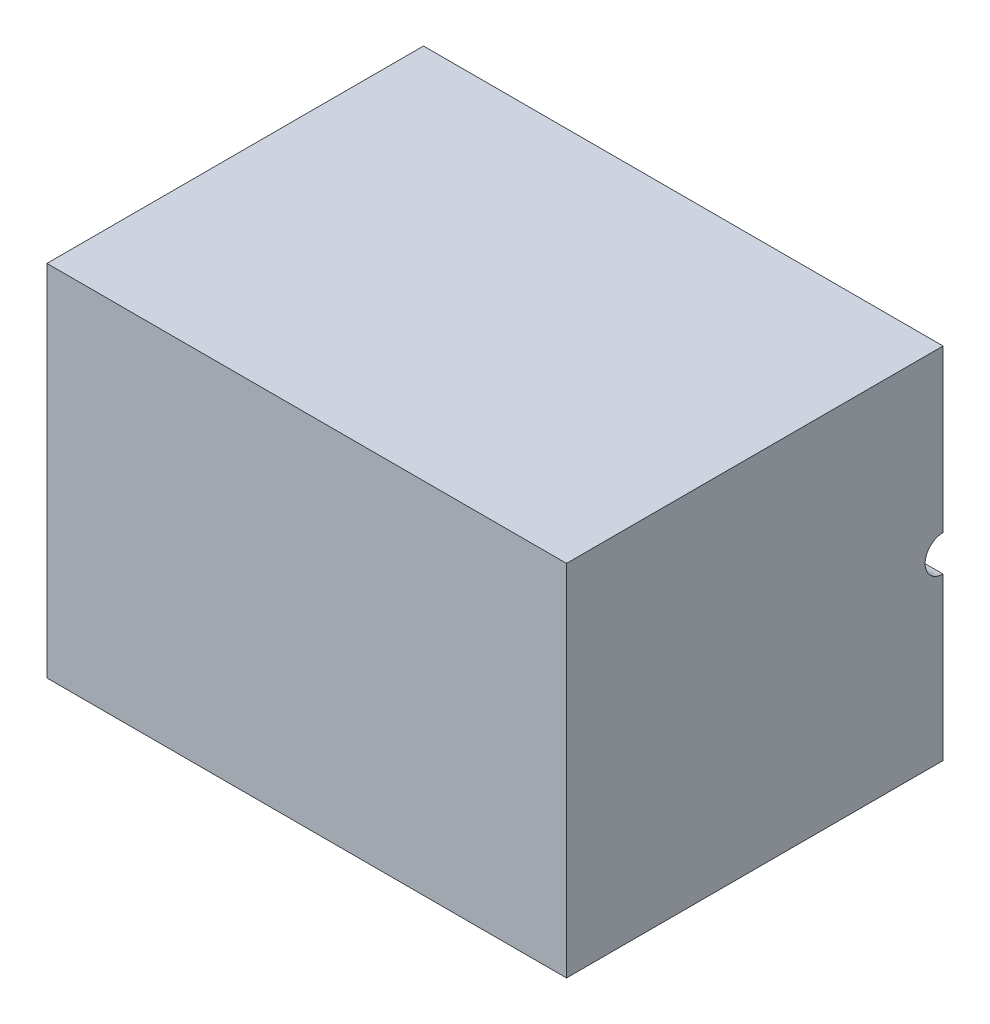
SolidWorks part; units mm, degrees
ref_plane "Front Plane" through (0, 0, 0) normal (0, 0, 1) x (1, 0, 0)
ref_plane "Top Plane" through (0, 0, 0) normal (0, 1, 0) x (1, 0, 0)
ref_plane "Right Plane" through (0, 0, 0) normal (1, 0, 0) x (0, 0, -1)
sketch "Sketch1" plane through (0, 0, 0) normal (0, 1, 0) x (1, 0, 0)
  line L1 (-72.3513, 52.4343) -> (72.3513, 52.4343)
  line L2 (-72.3513, 52.4343) -> (-72.3513, -52.4343)
  line L3 (-72.3513, -52.4343) -> (72.3513, -52.4343)
  line L4 (72.3513, 52.4343) -> (72.3513, -52.4343)
  point P0 (0, 0)
  dimension "D1" = 72.3513
  dimension "D2" = 72.3513
  dimension "D3" = 52.4343
  dimension "D4" = 52.4343
extrude "Boss-Extrude5" add sketch "Sketch1" along normal blind 100
sketch "Sketch14" plane through (0, 0, -52.4343) normal (0, 0, -1) x (-1, 0, 0)
  line L0 (-72.3513, 50) -> (-29.0038, 50)
  line L1 (-72.3513, 100) -> (-72.3513, 0) construction
  line L2 (-29.0038, 50) -> (-15.9053, 69.8816)
  line L3 (-15.9053, 69.8816) -> (9.0442, 69.8816)
  line L4 (9.0442, 69.8816) -> (23.3902, 50)
  line L5 (23.3902, 50) -> (72.3513, 50)
  line L6 (72.3513, 100) -> (72.3513, 0) construction
sweep "Cut-Sweep2" cut path "Sketch14" circular profile diameter 10 parameters "D3"=10
